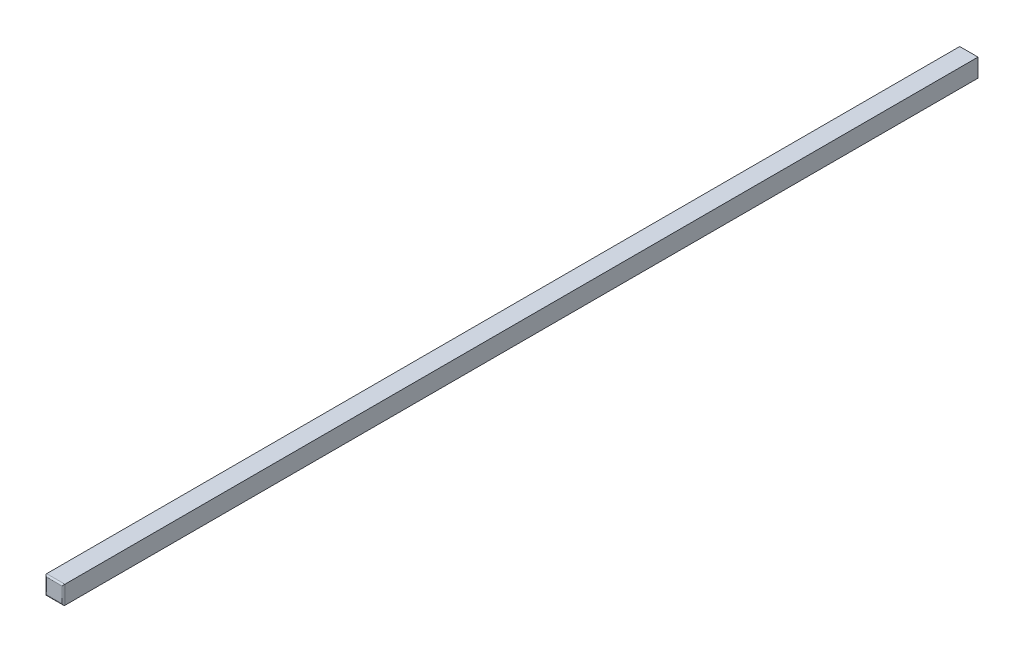
SolidWorks part; units mm, degrees
material "Plain Carbon Steel"
ref_plane "Front Plane" through (0, 0, 0) normal (0, 0, 1) x (1, 0, 0)
ref_plane "Top Plane" through (0, 0, 0) normal (0, 1, 0) x (1, 0, 0)
ref_plane "Right Plane" through (0, 0, 0) normal (1, 0, 0) x (0, 0, -1)
sketch "Sketch1" plane through (0, 0, 0) normal (0, 0, 1) x (1, 0, 0)
  line L0 (-3, 0) -> (3, 0) construction
  line L1 (0, -3) -> (0, 3) construction
  line L5 (-3, 3) -> (3, 3) construction
  line L7 (-3, 3) -> (-3, -3) construction
  line L8 (3, -3) -> (3, 3) construction
  line L13 (-3, -3) -> (3, -3) construction
  point P0 (0, 0)
  point P4 (0, 0)
  point P9 (0, 0)
  point P22 (0, 3)
  dimension "Thickness" = 6
  dimension "D1" = 6
sketch "Sketch2" plane through (0, 0, 0) normal (0, 1, 0) x (0, 0, -1)
  line L0 (150, 0) -> (-150, 0) construction
  line L2 (-150, 3) -> (150, 3) construction
  line L3 (-150, 3) -> (-150, -3) construction
  line L4 (-150, -3) -> (150, -3) construction
  line L5 (150, 3) -> (150, -3) construction
  line L6 (-150, 3) -> (150, -3) construction
  line L7 (-150, -3) -> (150, 3) construction
  point P4 (0, 0)
  point P7 (0, 0)
  point P12 (-143.1, 3)
  point P13 (143.1, 3)
  dimension "Length" = 300
  dimension "Width" = 6
  dimension "D1" = 6.9
  dimension "D2" = 6.9
sketch "Sketch3" plane through (0, 0, 0) normal (0, 0, 1) x (1, 0, 0)
  line L3 (-3, 3) -> (3, 3)
  line L17 (3, 3) -> (3, -3)
  line L18 (3, -3) -> (-3, -3)
  line L19 (-3, -3) -> (-3, 3)
extrude "Boss-Extrude1" add sketch "Sketch3" along normal mid plane 300
fillet "Fillet1" radius 0.5 4 edges at (0, 3, 150) (-3, 0, 150) (3, 0, 150) (0, -3, 150)
equation "\"D1@Boss-Extrude1\" = \"Length@Sketch2\""
equation "\"D1@Sketch1\"=\"Width@Sketch2\""
equation "\"D1@Sketch2\"=\"Width@Sketch2\"*1.15"
equation "\"D2@Sketch2\"=\"D1@Sketch2\""
